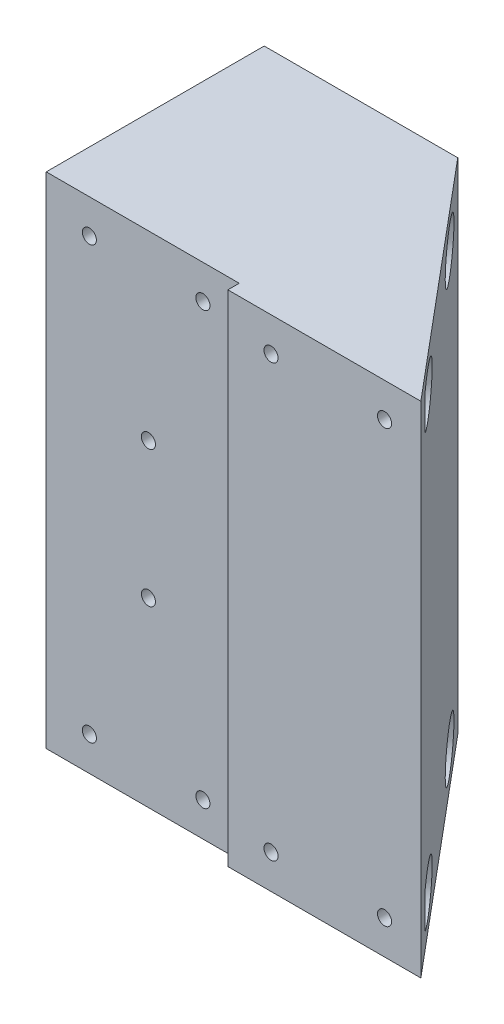
SolidWorks part; units mm, degrees
ref_plane "Front Plane" through (0, 0, 0) normal (0, 0, 1) x (1, 0, 0)
ref_plane "Top Plane" through (0, 0, 0) normal (0, 1, 0) x (1, 0, 0)
ref_plane "Right Plane" through (0, 0, 0) normal (1, 0, 0) x (0, 0, -1)
sketch "Sketch1" plane through (0, 0, 0) normal (0, 0, 1) x (1, 0, 0)
  line L1 (-42.5, -55) -> (42.5, -55)
  line L2 (-42.5, -55) -> (-42.5, 55)
  line L3 (-42.5, 55) -> (42.5, 55)
  line L4 (42.5, -55) -> (42.5, 55)
  line L5 (-42.5, -55) -> (42.5, 55) construction
  line L6 (-42.5, 55) -> (42.5, -55) construction
  point P0 (0, 0)
  dimension "D1" = 85
  dimension "D2" = 110
extrude "Boss-Extrude1" add sketch "Sketch1" along normal blind 50.5
sketch "Sketch2" plane through (0, 0, 50.5) normal (0, 0, 1) x (1, 0, 0)
  line L0 (-42.5, -55) -> (42.5, -55) construction
  line L1 (-42.5, 55) -> (0, 55)
  line L2 (-42.5, 55) -> (-42.5, -55)
  line L3 (-42.5, -55) -> (0, -55)
  line L4 (0, 55) -> (0, -55)
extrude "Cut-Extrude1" cut sketch "Sketch2" against normal blind 2.5
ref_plane "Plane1" through (0.0736, 0, -0.0618) normal (-0.766, 0, 0.6428) x (0, 1, 0)
sketch "Sketch3" plane through (0.0736, 0, -0.0618) normal (-0.766, 0, 0.6428) x (0, 1, 0)
  line L1 (-66.8163, 60.5011) -> (63.1837, 60.5011)
  line L2 (-66.8163, 60.5011) -> (-66.8163, -69.4989)
  line L3 (-66.8163, -69.4989) -> (63.1837, -69.4989)
  line L4 (63.1837, 60.5011) -> (63.1837, -69.4989)
  dimension "D1" = 130
  dimension "D2" = 130
extrude "Cut-Extrude2" cut sketch "Sketch3" against normal up to next
sketch "Sketch4" plane through (0, 0, 48) normal (0, 0, 1) x (1, 0, 0)
  circle A0 centre (-8, 47.5) radius 1.55 construction
  circle A1 centre (-33, 47.5) radius 1.55 construction
  circle A2 centre (-20, 15) radius 1.55 construction
  circle A3 centre (-20, -15) radius 1.55 construction
  circle A4 centre (-8, -47.5) radius 1.55 construction
  circle A5 centre (-33, -47.5) radius 1.55 construction
  circle A6 centre (-8, 47.5) radius 1.55
  circle A7 centre (-33, 47.5) radius 1.55
  circle A8 centre (-20, 15) radius 1.55
  circle A9 centre (-20, -15) radius 1.55
  circle A10 centre (-8, -47.5) radius 1.55
  circle A11 centre (-33, -47.5) radius 1.55
extrude "Cut-Extrude3" cut sketch "Sketch4" against normal up to next
sketch "Sketch5" plane through (0, 0, 50.5) normal (0, 0, 1) x (1, 0, 0)
  line L0 (9.5, 47.5) -> (34.5, 47.5) construction
  line L1 (9.5, 47.5) -> (9.5, -47.5) construction
  line L2 (0, -55) -> (0, 55) construction
  line L3 (42.5, 55) -> (0, 55) construction
  line L4 (9.5, 47.5) -> (34.5, 47.5) construction
  circle A0 centre (9.5, 47.5) radius 1.55
  circle A1 centre (34.5, 47.5) radius 1.55
  circle A2 centre (34.5, -47.5) radius 1.55
  circle A3 centre (9.5, -47.5) radius 1.55
  circle A4 centre (9.5, 47.5) radius 5
  circle A5 centre (34.5, 47.5) radius 5
  circle A6 centre (34.5, -47.5) radius 5
  circle A7 centre (9.5, -47.5) radius 5
  dimension "D1" = 3.1
  dimension "D8" = 10
  dimension "D4" = 25
  dimension "D5" = 95
  dimension "D6" = 9.5
  dimension "D7" = 7.5
  dimension "D11" = 25
  dimension "D2" = 2
  dimension "D3" = 2
  dimension "D9" = 2
  dimension "D10" = 2
extrude "Cut-Extrude5" cut sketch "Sketch5" against normal through all contours A0 | A1 | A2 | A3
ref_plane "Plane2" through (0, 0, -10) normal (0, 0, -1) x (-1, 0, 0)
sketch "Sketch9" plane through (0, 0, -10) normal (0, 0, -1) x (-1, 0, 0)
  circle A0 centre (-34.5, 47.5) radius 5
  circle A1 centre (-9.5, 47.5) radius 5
  circle A2 centre (-34.5, -47.5) radius 5
  circle A3 centre (-9.5, -47.5) radius 5
  dimension "D1" = 10
extrude "Cut-Extrude6" cut sketch "Sketch9" against normal blind 55
sketch "Sketch10" plane through (0, 0, 0) normal (0, 0, -1) x (-1, 0, 0)
  circle A0 centre (8, 47.5) radius 5
  circle A1 centre (33, 47.5) radius 5
  circle A2 centre (33, -47.5) radius 5
  circle A3 centre (8, -47.5) radius 5
  circle A4 centre (20, 15) radius 5
  circle A5 centre (20, -15) radius 5
  dimension "D1" = 10
extrude "Cut-Extrude7" cut sketch "Sketch10" against normal blind 40
